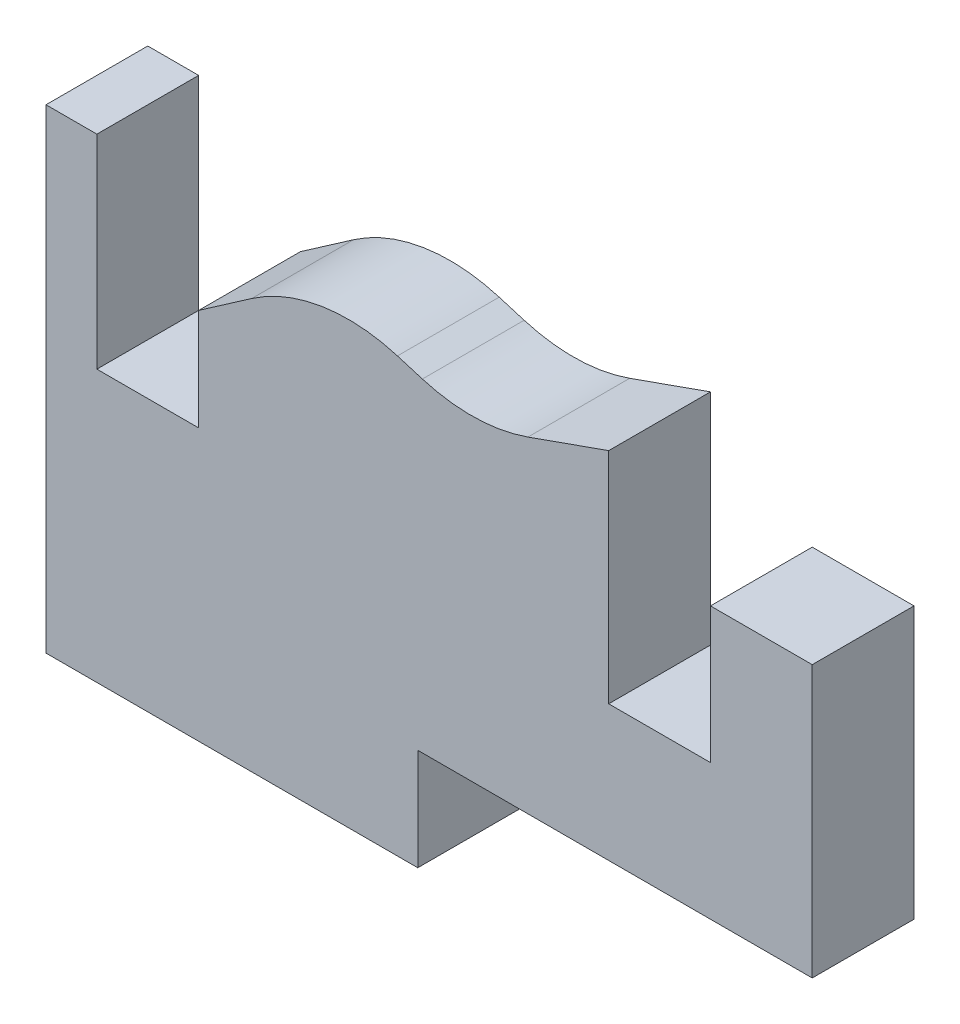
SolidWorks part; units mm, degrees
ref_plane "Front Plane" through (0, 0, 0) normal (0, 0, 1) x (1, 0, 0)
ref_plane "Top Plane" through (0, 0, 0) normal (0, 1, 0) x (1, 0, 0)
ref_plane "Right Plane" through (0, 0, 0) normal (1, 0, 0) x (0, 0, -1)
sketch "Sketch1" plane through (0, 0, 0) normal (0, 0, 1) x (1, 0, 0)
  line L0 (-18.6877, 18.7292) -> (-15.6877, 18.7292)
  line L1 (-15.6877, 18.7292) -> (-15.6877, 6.7292)
  line L2 (-15.6877, 6.7292) -> (-9.6877, 6.7292)
  line L3 (-9.6877, 6.7292) -> (-9.6877, 12.7292)
  line L4 (-9.6877, 12.7292) -> (-6.5562, 14.9036)
  line L5 (2.0314, 16.2647) -> (3.5037, 15.8212)
  line L6 (9.7269, 15.9703) -> (14.488, 17.657)
  line L7 (14.488, 17.657) -> (14.488, 4.7292)
  line L8 (14.488, 4.7292) -> (20.488, 4.7292)
  line L9 (20.488, 4.7292) -> (20.488, 12.7292)
  line L10 (20.488, 12.7292) -> (26.488, 12.7292)
  line L11 (26.488, 12.7292) -> (26.488, -3.2708)
  line L12 (26.488, -3.2708) -> (3.2312, -3.2708)
  line L13 (3.2312, -3.2708) -> (3.2312, -9.2708)
  line L14 (3.2312, -9.2708) -> (-18.6877, -9.2708)
  line L15 (-18.6877, -9.2708) -> (-18.6877, 18.7292)
  line L16 (-9.6877, 11.0881) -> (14.488, 11.0881) construction
  line L17 (14.488, 4.7292) -> (14.488, -3.2708) construction
  line L18 (14.488, 4.7292) -> (3.2312, 4.7292) construction
  arc A0 (3.5037, 15.8212) -> (9.7269, 15.9703) centre (6.3877, 25.3963) ccw
  arc A1 (-6.5562, 14.9036) -> (2.0314, 16.2647) centre (-0.8527, 6.6896) cw
  dimension "D1" = 10
extrude "Boss-Extrude1" add sketch "Sketch1" along normal blind 6
